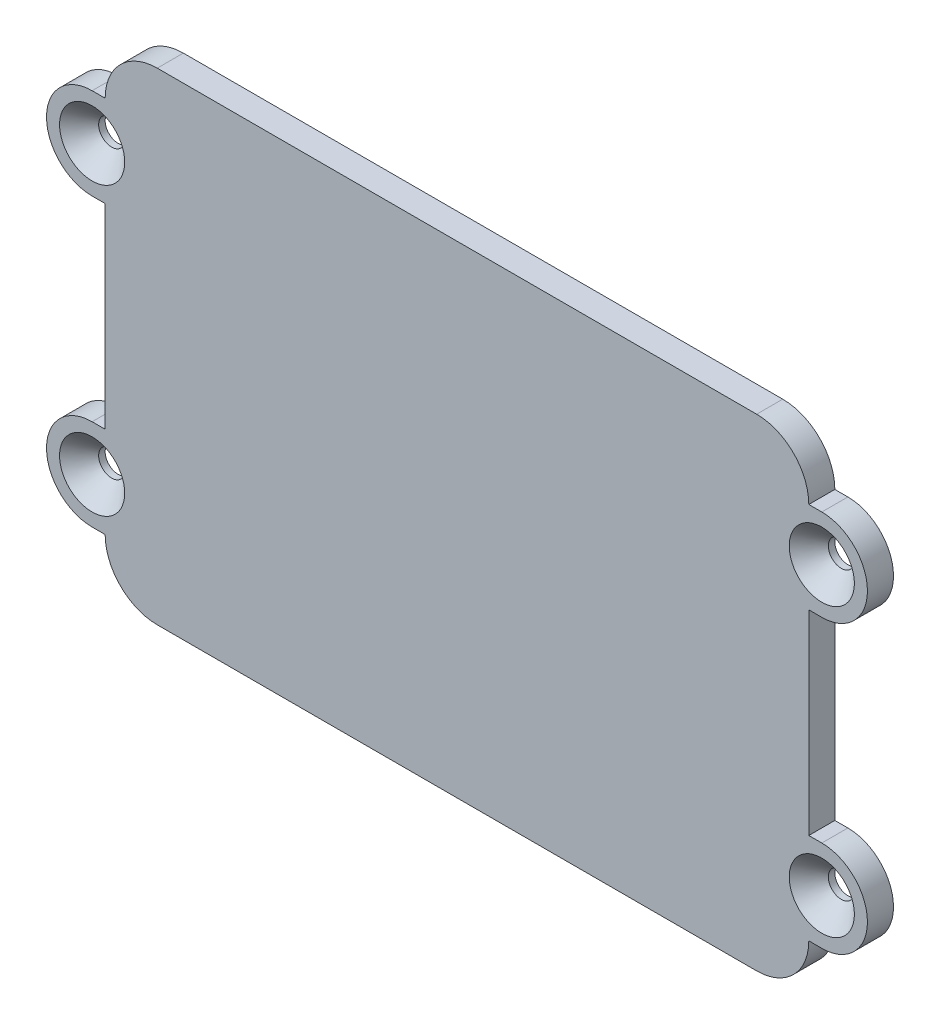
SolidWorks part; units mm, degrees
ref_plane "Piano frontale" through (0, 0, 0) normal (0, 0, 1) x (1, 0, 0)
ref_plane "Piano superiore" through (0, 0, 0) normal (0, 1, 0) x (1, 0, 0)
ref_plane "Piano destro" through (0, 0, 0) normal (1, 0, 0) x (0, 0, -1)
sketch "Schizzo1" plane through (0, 0, 0) normal (0, 0, 1) x (1, 0, 0)
  line L12 (-23, -18.5) -> (23, -18.5)
  line L13 (27, -14.5) -> (28, -14.5)
  line L14 (28, -7.5) -> (27, -7.5)
  line L15 (27, -7.5) -> (27, 7.5)
  line L16 (27, 7.5) -> (28, 7.5)
  line L17 (28, 14.5) -> (27, 14.5)
  line L18 (23, 18.5) -> (-23, 18.5)
  line L19 (-27, 14.5) -> (-28, 14.5)
  line L20 (-28, 7.5) -> (-27, 7.5)
  line L21 (-27, 7.5) -> (-27, -7.5)
  line L22 (-27, -7.5) -> (-28, -7.5)
  line L23 (-28, -14.5) -> (-27, -14.5)
  line L24 (-23, -18.5) -> (23, -18.5)
  line L25 (27, -14.5) -> (28, -14.5)
  line L26 (28, -7.5) -> (27, -7.5)
  line L27 (27, -7.5) -> (27, 7.5)
  line L28 (27, 7.5) -> (28, 7.5)
  line L29 (28, 14.5) -> (27, 14.5)
  line L30 (23, 18.5) -> (-23, 18.5)
  line L31 (-27, 14.5) -> (-28, 14.5)
  line L32 (-28, 7.5) -> (-27, 7.5)
  line L33 (-27, 7.5) -> (-27, -7.5)
  line L34 (-27, -7.5) -> (-28, -7.5)
  line L35 (-28, -14.5) -> (-27, -14.5)
  circle A0 centre (-28, 11) radius 1
  circle A1 centre (-28, -11) radius 1
  circle A2 centre (28, -11) radius 1
  circle A3 centre (28, 11) radius 1
  arc A8 (23, -18.5) -> (27, -14.5) centre (23, -14.5) ccw
  arc A9 (28, -14.5) -> (28, -7.5) centre (28, -11) ccw
  arc A10 (28, 7.5) -> (28, 14.5) centre (28, 11) ccw
  arc A11 (27, 14.5) -> (23, 18.5) centre (23, 14.5) ccw
  arc A12 (-23, 18.5) -> (-27, 14.5) centre (-23, 14.5) ccw
  arc A13 (-28, 14.5) -> (-28, 7.5) centre (-28, 11) ccw
  arc A14 (-28, -7.5) -> (-28, -14.5) centre (-28, -11) ccw
  arc A15 (-27, -14.5) -> (-23, -18.5) centre (-23, -14.5) ccw
  arc A16 (23, -18.5) -> (27, -14.5) centre (23, -14.5) ccw
  arc A17 (28, -14.5) -> (28, -7.5) centre (28, -11) ccw
  arc A18 (28, 7.5) -> (28, 14.5) centre (28, 11) ccw
  arc A19 (27, 14.5) -> (23, 18.5) centre (23, 14.5) ccw
  arc A20 (-23, 18.5) -> (-27, 14.5) centre (-23, 14.5) ccw
  arc A21 (-28, 14.5) -> (-28, 7.5) centre (-28, 11) ccw
  arc A22 (-28, -7.5) -> (-28, -14.5) centre (-28, -11) ccw
  arc A23 (-27, -14.5) -> (-23, -18.5) centre (-23, -14.5) ccw
  dimension "D2" = 2
  dimension "D1" = 0
extrude "Estrusione-Estrusione1" add sketch "Schizzo1" along normal blind 2
chamfer "Smusso1" distance 1.5 angle 45 4 edges at (-27, -11, 2) (29, -11, 2) (29, 11, 2) (-27, 11, 2)
